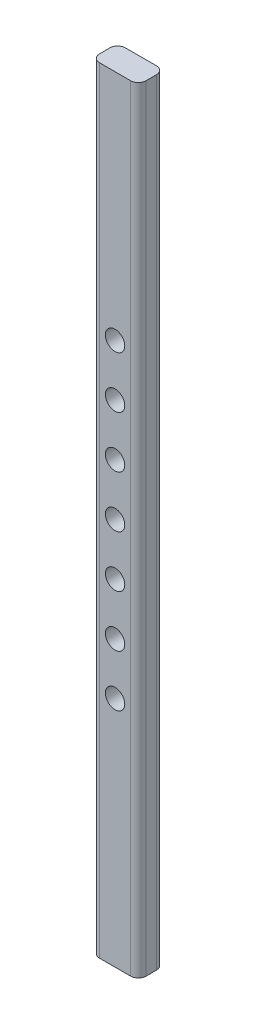
SolidWorks part; units mm, degrees
ref_plane "Alzado" through (0, 0, 0) normal (0, 0, 1) x (1, 0, 0)
ref_plane "Planta" through (0, 0, 0) normal (0, 1, 0) x (1, 0, 0)
ref_plane "Vista lateral" through (0, 0, 0) normal (1, 0, 0) x (0, 0, -1)
sketch "Croquis1" plane through (0, 0, 0) normal (0, 0, 1) x (1, 0, 0)
  line L1 (-9, 150) -> (9, 150)
  line L2 (-9, 150) -> (-9, -150)
  line L3 (-9, -150) -> (9, -150)
  line L4 (9, 150) -> (9, -150)
  line L5 (-9, 150) -> (9, -150) construction
  line L6 (-9, -150) -> (9, 150) construction
  point P0 (0, 0)
  dimension "D1" = 300
  dimension "D2" = 18
extrude "Saliente-Extruir1" add sketch "Croquis1" along normal mid plane 10
fillet "Redondeo2" radius 3 4 edges at (-9, 0, 5) (-9, 0, -5) (9, 0, 5) (9, 0, -5)
sketch "Croquis2" plane through (0, 0, 5) normal (0, 0, 1) x (1, 0, 0)
  line L0 (0, 150) -> (0, -150) construction
  line L1 (6, 150) -> (-6, 150) construction
  line L2 (-6, -150) -> (6, -150) construction
  circle A0 centre (0, 0) radius 3.7479
  circle A1 centre (0, 20) radius 3.7479
  circle A2 centre (0, 40) radius 3.7479
  circle A3 centre (0, 60) radius 3.7479
  circle A4 centre (0, -20) radius 3.7479
  circle A5 centre (0, 0) radius 3.7479
  circle A6 centre (0, 20) radius 3.7479
  circle A7 centre (0, -60) radius 3.7479
  circle A8 centre (0, -40) radius 3.7479
  circle A9 centre (0, -20) radius 3.7479
  circle A10 centre (0, -40) radius 3.7479
extrude "Cortar-Extruir1" cut sketch "Croquis2" against normal blind 10 contours A3 | A2 | A1 | A0 | A4 | A8 | A7
